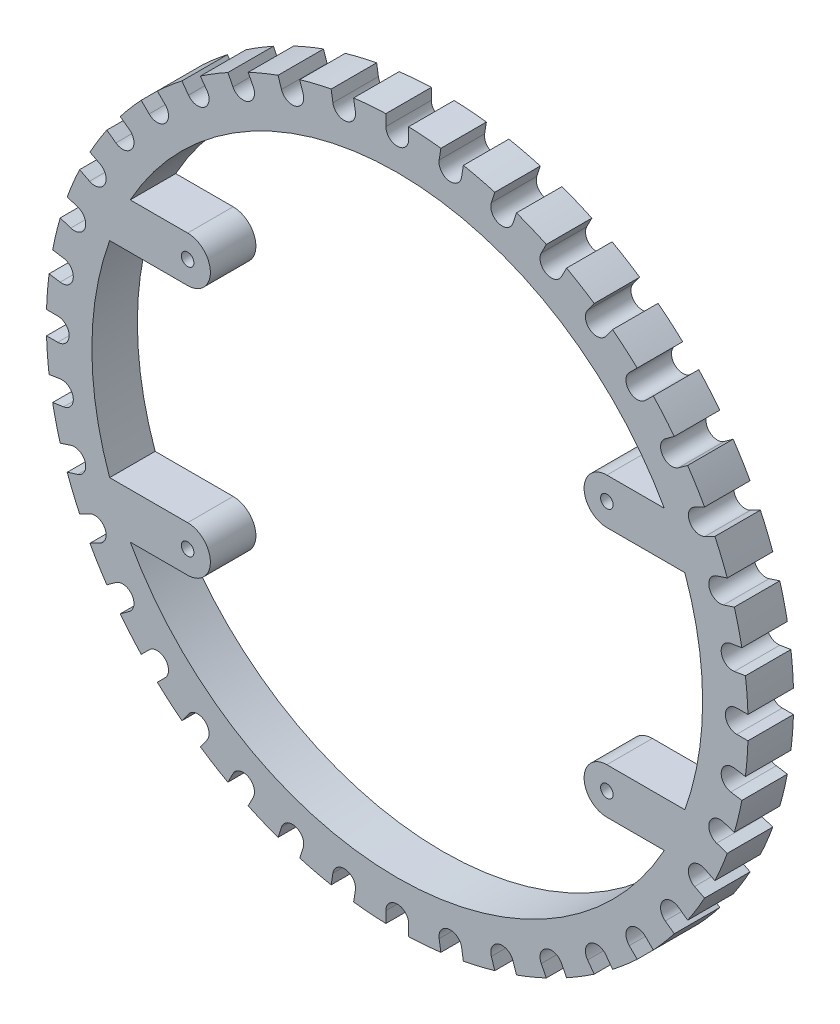
SolidWorks part; units mm, degrees
ref_plane "Front Plane" through (0, 0, 0) normal (0, 0, 1) x (1, 0, 0)
ref_plane "Top Plane" through (0, 0, 0) normal (0, 1, 0) x (1, 0, 0)
ref_plane "Right Plane" through (0, 0, 0) normal (1, 0, 0) x (0, 0, -1)
sketch "Sketch1" plane through (0, 0, 0) normal (0, 0, 1) x (1, 0, 0)
  line L0 (-58.5, -35) -> (58.5, -35) construction
  line L3 (0, 0) -> (0, -97.925) construction
  line L4 (-3.175, -94.75) -> (-3.175, -97.8735)
  line L5 (3.175, -94.75) -> (3.175, -97.8735)
  line L6 (-58.5, -28.65) -> (-80.265, -28.65)
  line L7 (-58.5, -41.35) -> (-74.5217, -41.35)
  line L8 (-11.6863, -94.0801) -> (-12.1749, -97.1652)
  line L9 (-17.9581, -93.0868) -> (-18.4467, -96.1719)
  line L10 (-26.2598, -91.0937) -> (-27.225, -94.0644)
  line L11 (-32.299, -89.1315) -> (-33.2642, -92.1021)
  line L12 (-40.1867, -85.8643) -> (-41.6047, -88.6474)
  line L13 (-45.8445, -82.9814) -> (-47.2626, -85.7645)
  line L14 (-53.124, -78.5206) -> (-54.96, -81.0476)
  line L15 (-58.2613, -74.7881) -> (-60.0972, -77.3151)
  line L16 (-64.7533, -69.2434) -> (-66.962, -71.4521)
  line L17 (-69.2434, -64.7533) -> (-71.4521, -66.962)
  line L18 (-74.7881, -58.2613) -> (-77.3151, -60.0972)
  line L19 (-78.5206, -53.124) -> (-81.0476, -54.96)
  line L20 (-82.9814, -45.8445) -> (-85.7645, -47.2626)
  line L21 (-85.8643, -40.1867) -> (-88.6474, -41.6047)
  line L22 (-89.1315, -32.299) -> (-92.1021, -33.2642)
  line L23 (-91.0937, -26.2598) -> (-94.0644, -27.225)
  line L24 (-93.0868, -17.9581) -> (-96.1719, -18.4467)
  line L25 (-94.0801, -11.6863) -> (-97.1652, -12.1749)
  line L26 (-94.75, -3.175) -> (-97.8735, -3.175)
  line L27 (-94.75, 3.175) -> (-97.8735, 3.175)
  line L28 (-94.0801, 11.6863) -> (-97.1652, 12.1749)
  line L29 (-93.0868, 17.9581) -> (-96.1719, 18.4467)
  line L30 (-91.0937, 26.2598) -> (-94.0644, 27.225)
  line L31 (-89.1315, 32.299) -> (-92.1021, 33.2642)
  line L32 (-85.8643, 40.1867) -> (-88.6474, 41.6047)
  line L33 (-82.9814, 45.8445) -> (-85.7645, 47.2626)
  line L34 (-78.5206, 53.124) -> (-81.0476, 54.96)
  line L35 (-74.7881, 58.2613) -> (-77.3151, 60.0972)
  line L36 (-69.2434, 64.7533) -> (-71.4521, 66.962)
  line L37 (-64.7533, 69.2434) -> (-66.962, 71.4521)
  line L38 (-58.2613, 74.7881) -> (-60.0972, 77.3151)
  line L39 (-53.124, 78.5206) -> (-54.96, 81.0476)
  line L40 (-45.8445, 82.9814) -> (-47.2626, 85.7645)
  line L41 (-40.1867, 85.8643) -> (-41.6047, 88.6474)
  line L42 (-32.299, 89.1315) -> (-33.2642, 92.1021)
  line L43 (-26.2598, 91.0937) -> (-27.225, 94.0644)
  line L44 (-17.9581, 93.0868) -> (-18.4467, 96.1719)
  line L45 (-11.6863, 94.0801) -> (-12.1749, 97.1652)
  line L46 (-3.175, 94.75) -> (-3.175, 97.8735)
  line L47 (3.175, 94.75) -> (3.175, 97.8735)
  line L48 (11.6863, 94.0801) -> (12.1749, 97.1652)
  line L49 (17.9581, 93.0868) -> (18.4467, 96.1719)
  line L50 (26.2598, 91.0937) -> (27.225, 94.0644)
  line L51 (32.299, 89.1315) -> (33.2642, 92.1021)
  line L52 (40.1867, 85.8643) -> (41.6047, 88.6474)
  line L53 (45.8445, 82.9814) -> (47.2626, 85.7645)
  line L54 (53.124, 78.5206) -> (54.96, 81.0476)
  line L55 (58.2613, 74.7881) -> (60.0972, 77.3151)
  line L56 (64.7533, 69.2434) -> (66.962, 71.4521)
  line L57 (69.2434, 64.7533) -> (71.4521, 66.962)
  line L58 (74.7881, 58.2613) -> (77.3151, 60.0972)
  line L59 (78.5206, 53.124) -> (81.0476, 54.96)
  line L60 (82.9814, 45.8445) -> (85.7645, 47.2626)
  line L61 (85.8643, 40.1867) -> (88.6474, 41.6047)
  line L62 (89.1315, 32.299) -> (92.1021, 33.2642)
  line L63 (91.0937, 26.2598) -> (94.0644, 27.225)
  line L64 (93.0868, 17.9581) -> (96.1719, 18.4467)
  line L65 (94.0801, 11.6863) -> (97.1652, 12.1749)
  line L66 (94.75, 3.175) -> (97.8735, 3.175)
  line L67 (94.75, -3.175) -> (97.8735, -3.175)
  line L68 (94.0801, -11.6863) -> (97.1652, -12.1749)
  line L69 (93.0868, -17.9581) -> (96.1719, -18.4467)
  line L70 (91.0937, -26.2598) -> (94.0644, -27.225)
  line L71 (89.1315, -32.299) -> (92.1021, -33.2642)
  line L72 (85.8643, -40.1867) -> (88.6474, -41.6047)
  line L73 (82.9814, -45.8445) -> (85.7645, -47.2626)
  line L74 (78.5206, -53.124) -> (81.0476, -54.96)
  line L75 (74.7881, -58.2613) -> (77.3151, -60.0972)
  line L76 (69.2434, -64.7533) -> (71.4521, -66.962)
  line L77 (64.7533, -69.2434) -> (66.962, -71.4521)
  line L78 (58.2613, -74.7881) -> (60.0972, -77.3151)
  line L79 (53.124, -78.5206) -> (54.96, -81.0476)
  line L80 (45.8445, -82.9814) -> (47.2626, -85.7645)
  line L81 (40.1867, -85.8643) -> (41.6047, -88.6474)
  line L82 (32.299, -89.1315) -> (33.2642, -92.1021)
  line L83 (26.2598, -91.0937) -> (27.225, -94.0644)
  line L84 (17.9581, -93.0868) -> (18.4467, -96.1719)
  line L85 (11.6863, -94.0801) -> (12.1749, -97.1652)
  line L86 (58.5, -41.35) -> (74.5217, -41.35)
  line L87 (58.5, -28.65) -> (80.265, -28.65)
  line L88 (-85.225, 0) -> (85.225, 0) construction
  line L89 (58.5, 28.65) -> (80.265, 28.65)
  line L90 (58.5, 41.35) -> (74.5217, 41.35)
  line L91 (-58.5, 28.65) -> (-80.265, 28.65)
  line L92 (-58.5, 41.35) -> (-74.5217, 41.35)
  circle A0 centre (0, 0) radius 98.425 construction
  circle A1 centre (0, 0) radius 97.925
  circle A44 centre (0, -94.75) radius 3.175
  circle A45 centre (-14.8222, -93.5835) radius 3.175
  circle A46 centre (-29.2794, -90.1126) radius 3.175
  circle A47 centre (-43.0156, -84.4229) radius 3.175
  circle A48 centre (-55.6927, -76.6544) radius 3.175
  circle A49 centre (-66.9984, -66.9984) radius 3.175
  circle A50 centre (-76.6544, -55.6927) radius 3.175
  circle A51 centre (-84.4229, -43.0156) radius 3.175
  circle A52 centre (-90.1126, -29.2794) radius 3.175
  circle A53 centre (-93.5835, -14.8222) radius 3.175
  circle A54 centre (-94.75, 0) radius 3.175
  circle A55 centre (-93.5835, 14.8222) radius 3.175
  circle A56 centre (-90.1126, 29.2794) radius 3.175
  circle A57 centre (-84.4229, 43.0156) radius 3.175
  circle A58 centre (-76.6544, 55.6927) radius 3.175
  circle A59 centre (-66.9984, 66.9984) radius 3.175
  circle A60 centre (-55.6927, 76.6544) radius 3.175
  circle A61 centre (-43.0156, 84.4229) radius 3.175
  circle A62 centre (-29.2794, 90.1126) radius 3.175
  circle A63 centre (-14.8222, 93.5835) radius 3.175
  circle A64 centre (0, 94.75) radius 3.175
  circle A65 centre (14.8222, 93.5835) radius 3.175
  circle A66 centre (29.2794, 90.1126) radius 3.175
  circle A67 centre (43.0156, 84.4229) radius 3.175
  circle A68 centre (55.6927, 76.6544) radius 3.175
  circle A69 centre (66.9984, 66.9984) radius 3.175
  circle A70 centre (76.6544, 55.6927) radius 3.175
  circle A71 centre (84.4229, 43.0156) radius 3.175
  circle A72 centre (90.1126, 29.2794) radius 3.175
  circle A73 centre (93.5835, 14.8222) radius 3.175
  circle A74 centre (94.75, 0) radius 3.175
  circle A75 centre (93.5835, -14.8222) radius 3.175
  circle A76 centre (90.1126, -29.2794) radius 3.175
  circle A77 centre (84.4229, -43.0156) radius 3.175
  circle A78 centre (76.6544, -55.6927) radius 3.175
  circle A79 centre (66.9984, -66.9984) radius 3.175
  circle A80 centre (55.6927, -76.6544) radius 3.175
  circle A81 centre (43.0156, -84.4229) radius 3.175
  circle A82 centre (29.2794, -90.1126) radius 3.175
  circle A83 centre (14.8222, -93.5835) radius 3.175
  arc A84 (-74.5217, -41.35) -> (74.5217, -41.35) centre (0, 0) ccw
  circle A85 centre (-58.5, -35) radius 1.75
  arc A87 (-58.5, -41.35) -> (-58.5, -28.65) centre (-58.5, -35) ccw
  arc A88 (-74.5217, -41.35) -> (74.5217, -41.35) centre (0, 0) ccw
  circle A89 centre (58.5, -35) radius 1.75
  arc A90 (58.5, -41.35) -> (58.5, -28.65) centre (58.5, -35) cw
  arc A91 (80.265, -28.65) -> (80.265, 28.65) centre (0, 0) ccw
  arc A92 (80.265, -28.65) -> (80.265, 28.65) centre (0, 0) ccw
  circle A93 centre (58.5, 35) radius 1.75
  arc A94 (58.5, 41.35) -> (58.5, 28.65) centre (58.5, 35) ccw
  circle A95 centre (-58.5, 35) radius 1.75
  arc A96 (-58.5, 41.35) -> (-58.5, 28.65) centre (-58.5, 35) cw
  arc A97 (-80.265, 28.65) -> (-80.265, -28.65) centre (0, 0) ccw
  arc A98 (-80.265, 28.65) -> (-80.265, -28.65) centre (0, 0) ccw
  arc A99 (74.5217, 41.35) -> (-74.5217, 41.35) centre (0, 0) ccw
  arc A100 (74.5217, 41.35) -> (-74.5217, 41.35) centre (0, 0) ccw
  point P4 (0, -35)
  point P259 (0, 0)
  dimension "D1" = 196.85
  dimension "D2" = 0.5
  dimension "D3" = 12.7
  dimension "D5" = 40
  dimension "D6" = 6.35
  dimension "D4" = 3.5
  dimension "D8" = 117
  dimension "D9" = 12.7
  dimension "D7" = 35
extrude "Boss-Extrude1" add sketch "Sketch1" along normal blind 12.7
